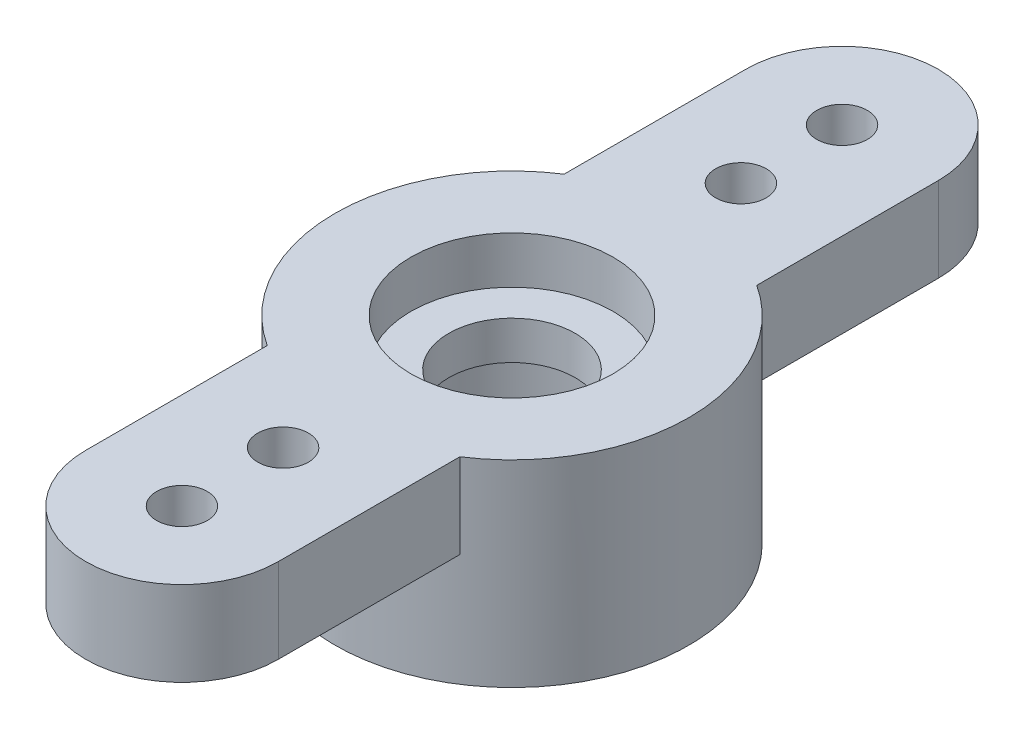
SolidWorks part; units mm, degrees
ref_plane "Front Plane" through (0, 0, 0) normal (0, 0, 1) x (1, 0, 0)
ref_plane "Top Plane" through (0, 0, 0) normal (0, 1, 0) x (1, 0, 0)
ref_plane "Right Plane" through (0, 0, 0) normal (1, 0, 0) x (0, 0, -1)
sketch "Sketch1" plane through (0, 0, 0) normal (0, 0, 1) x (1, 0, 0)
  line L0 (2.25, 0) -> (1.25, 0)
  line L1 (1.25, 0) -> (1.25, 0.76)
  line L2 (1.25, 0.76) -> (2, 0.76)
  line L3 (2, 0.76) -> (2, 1.69)
  line L4 (2, 1.69) -> (3.5, 1.69)
  line L5 (3.5, 1.69) -> (3.5, -2.21)
  line L6 (3.5, -2.21) -> (2.25, -2.21)
  line L7 (2.25, -2.21) -> (2.25, 0)
  line L8 (0, 0) -> (0, 1.69) construction
  line L9 (0, 0) -> (0, -2.21) construction
  dimension "D1" = 7
  dimension "D2" = 3.9
  dimension "D3" = 0.93
  dimension "D4" = 1.5
  dimension "D5" = 2.21
  dimension "D6" = 2.5
  dimension "D7" = 4.5
revolve "Revolve1" add sketch "Sketch1" angle 360 about L9
sketch "Sketch2" plane through (0, 1.69, 0) normal (0, 1, 0) x (1, 0, 0)
  line L0 (0, 6.5278) -> (0, -6.5278) construction
  line L1 (1.905, 6.5278) -> (1.905, -6.5278) construction
  line L2 (-1.905, 6.5278) -> (-1.905, -6.5278) construction
  line L3 (-1.905, 6.5278) -> (-1.905, 2.9361)
  line L4 (1.905, 6.5278) -> (1.905, 2.9361)
  arc A0 (1.905, 6.5278) -> (-1.905, 6.5278) centre (0, 6.5278) ccw construction
  arc A1 (-1.905, -6.5278) -> (1.905, -6.5278) centre (0, -6.5278) ccw construction
  arc A2 (-1.905, 6.5278) -> (1.905, 6.5278) centre (0, 6.5278) cw
  circle A3 centre (0, 0) radius 3.5 construction
  arc A4 (-1.905, 2.9361) -> (1.905, 2.9361) centre (0, 0) cw
  circle A5 centre (0, 6.5278) radius 0.5
  circle A6 centre (0, 4.5278) radius 0.5
  point P3 (0, 0)
  point P8 (0, -8.4328)
  point P9 (0, 8.4328)
  dimension "D4" = 1
  dimension "D1" = 3.81
  dimension "D2" = 16.8656
  dimension "D3" = 2
extrude "Boss-Extrude1" add sketch "Sketch2" against normal blind 1.675
pattern_circular "CirPattern1" count 2 over 360 about axis through (0, 0, 0) along (0, 1, 0) of "Boss-Extrude1"
sketch "Sketch3" plane through (0, 0.015, 0) normal (0, -1, 0) x (1, 0, 0)
  line L0 (0.927, -3.375) -> (16.7389, -1.9295)
  line L1 (0.927, 3.375) -> (16.7389, 1.9295)
  arc A0 (0.927, 3.375) -> (0.927, -3.375) centre (0, 0) cw
  circle A1 centre (0, 0) radius 3.5 construction
  arc A2 (16.7389, 1.9295) -> (16.7389, -1.9295) centre (16.5625, 0) cw
  circle A3 centre (16.5625, 0) radius 0.5
  circle A4 centre (14.5625, 0) radius 0.5
  circle A5 centre (12.5625, 0) radius 0.5
  circle A6 centre (10.5625, 0) radius 0.5
  circle A7 centre (8.5625, 0) radius 0.5
  circle A8 centre (6.5625, 0) radius 0.5
  circle A9 centre (4.5625, 0) radius 0.5
  point P8 (18.5, 0)
  point P10 (3.5, 0)
  dimension "D2" = 1.9375
  dimension "D4" = 1
  dimension "D1" = 15
  dimension "D3" = 6.75
  dimension "D6" = 12
  dimension "D5" = 7
extrude "Boss-Extrude2" [suppressed] add sketch "Sketch3" against normal up to surface (1.675 mm away)
sketch "Sketch4" [suppressed] plane through (0, 0.015, 0) normal (0, -1, 0) x (1, 0, 0)
  line L0 (-1.905, 2.9361) -> (-14.2201, 1.9311)
  line L1 (-14.2201, -1.9311) -> (-1.905, -2.9361)
  arc A0 (-14.2201, 1.9311) -> (-14.2201, -1.9311) centre (-14.0625, 0) ccw
  circle A1 centre (-14.0625, 0) radius 0.5
  circle A2 centre (-11.5625, 0) radius 0.5
  circle A3 centre (-9.0625, 0) radius 0.5
  circle A4 centre (-6.5625, 0) radius 0.5
  circle A5 centre (-4.0625, 0) radius 0.5
  circle A6 centre (4.5625, 0) radius 0.5 construction
  arc A7 (-1.905, 2.9361) -> (-1.905, -2.9361) centre (0, 0) ccw
  arc A8 (16.7389, -1.9295) -> (16.7389, 1.9295) centre (16.5625, 0) ccw construction
  point P5 (-16, 0)
  point P21 (-3.5, 0)
  dimension "D2" = 10
  dimension "D3" = 12.5
  dimension "D1" = 5
extrude "Boss-Extrude3" [suppressed] add sketch "Sketch4" against normal up to surface (1.675 mm away)
